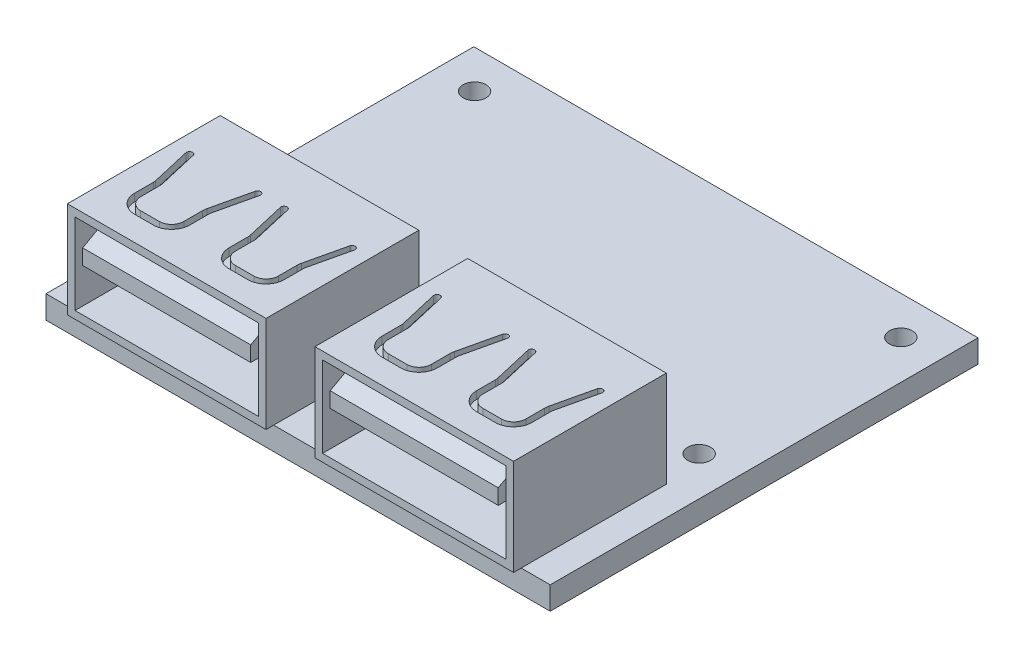
SolidWorks part; units mm, degrees
material "5V_BUCK_AVG"
ref_plane "Front Plane" through (0, 0, 0) normal (0, 0, 1) x (1, 0, 0)
ref_plane "Top Plane" through (0, 0, 0) normal (0, 1, 0) x (1, 0, 0)
ref_plane "Right Plane" through (0, 0, 0) normal (1, 0, 0) x (0, 0, -1)
sketch "Sketch1" plane through (0, 0, 0) normal (0, 1, 0) x (1, 0, 0)
  line L0 (-13.2, 4.318) -> (-13.2, 18.4768) construction
  line L1 (-16.5, -14) -> (16.5, -14)
  line L2 (-16.5, -14) -> (-16.5, 14)
  line L3 (-16.5, 14) -> (16.5, 14)
  line L4 (16.5, -14) -> (16.5, 14)
  line L5 (-16.5, -14) -> (16.5, 14) construction
  line L6 (-16.5, 14) -> (16.5, -14) construction
  line L7 (13.2, 0.5167) -> (13.2, 50000.5167) construction
  line L8 (-0.8528, 10.75) -> (49999.1472, 10.75) construction
  line L9 (-1.2363, -0.95) -> (49998.7637, -0.95) construction
  line L10 (0, 0) -> (50000, 0) construction
  line L11 (0, 0) -> (0, 50000) construction
  circle A0 centre (-13.95, 11.5) radius 0.75
  circle A1 centre (13.95, 11.5) radius 0.75
  circle A2 centre (13.95, -1.7) radius 0.75
  circle A3 centre (-13.95, -1.7) radius 0.75
  point P0 (0, 0)
  dimension "D3" = 1.5
  dimension "D1" = 33
  dimension "D2" = 28
  dimension "D4" = 26.4
  dimension "D5" = 11.7
  dimension "D6" = 2.5
extrude "Boss-Extrude1" add sketch "Sketch1" along normal blind 1.5
sketch "Sketch2" plane through (0, 1.5, 0) normal (0, 1, 0) x (1, 0, 0)
  line L0 (0, 0) -> (0, -50000) construction
  line L1 (-1.6, -4.5) -> (-14.6, -4.5)
  line L2 (-1.6, -4.5) -> (-1.6, -14.5)
  line L3 (-1.6, -14.5) -> (-14.6, -14.5)
  line L4 (-14.6, -4.5) -> (-14.6, -14.5)
  line L5 (-1.6, -4.5) -> (-14.6, -14.5) construction
  line L6 (-1.6, -14.5) -> (-14.6, -4.5) construction
  line L7 (-16.5, -14) -> (16.5, -14) construction
  point P0 (-8.1, -9.5)
  dimension "D1" = 13
  dimension "D2" = 10
  dimension "D3" = 1.6
  dimension "D4" = 0.5
extrude "Boss-Extrude2" add sketch "Sketch2" along normal blind 6.3
sketch "Sketch3" plane through (0, 0, 14.5) normal (0, 0, 1) x (1, 0, 0)
  line L0 (-14.1, 2) -> (-2.1, 2)
  line L1 (-2.1, 2) -> (-2.1, 7.3)
  line L2 (-2.1, 7.3) -> (-14.1, 7.3)
  line L3 (-14.1, 7.3) -> (-14.1, 2)
  line L4 (-14.6, 1.5) -> (-1.6, 1.5)
  line L5 (-1.6, 1.5) -> (-1.6, 7.8)
  line L6 (-1.6, 7.8) -> (-14.6, 7.8)
  line L7 (-14.6, 7.8) -> (-14.6, 1.5)
  line L8 (-14.6, 1.5) -> (-1.6, 1.5) construction
  line L9 (-1.6, 1.5) -> (-1.6, 7.8) construction
  line L10 (-1.6, 7.8) -> (-14.6, 7.8) construction
  line L11 (-14.6, 7.8) -> (-14.6, 1.5) construction
  dimension "D1" = 0
  dimension "D2" = 0.5
extrude "Cut-Extrude1" cut sketch "Sketch3" against normal offset from surface (9.5 mm away) 0.5 up to face at (-8.1, 4.65, 4.5)
sketch "Sketch4" plane through (0, 7.8, 0) normal (0, 1, 0) x (1, 0, 0)
  line L0 (-8.1, -4.5) -> (-8.1, -6.962) construction
  line L1 (-14.6, -4.5) -> (-14.6, -14) construction
  line L2 (-11.1939, -4.5) -> (-11.1939, -7.5186) construction
  line L3 (-13.4201, -7.6886) -> (-12.8274, -10.2519) construction
  line L4 (-12.8017, -10.4772) -> (-12.8017, -11.6975) construction
  line L5 (-11.8017, -12.6975) -> (-10.5861, -12.6975) construction
  line L6 (-9.5861, -10.4772) -> (-9.5861, -11.6975) construction
  line L7 (-8.9678, -7.6886) -> (-9.5604, -10.2519) construction
  line L8 (-13.6149, -7.7337) -> (-13.0223, -10.297)
  line L9 (-13.0017, -10.4772) -> (-13.0017, -11.6975)
  line L10 (-11.8017, -12.8975) -> (-10.5861, -12.8975)
  line L11 (-9.3861, -10.4772) -> (-9.3861, -11.6975)
  line L12 (-8.7729, -7.7337) -> (-9.3656, -10.297)
  line L13 (-13.2252, -7.6436) -> (-12.6325, -10.2069)
  line L14 (-12.6017, -10.4772) -> (-12.6017, -11.6975)
  line L15 (-11.8017, -12.4975) -> (-10.5861, -12.4975)
  line L16 (-9.7861, -10.4772) -> (-9.7861, -11.6975)
  line L17 (-9.1626, -7.6436) -> (-9.7553, -10.2069)
  line L18 (-7.2322, -7.6886) -> (-6.6396, -10.2519) construction
  line L19 (-6.6139, -10.4772) -> (-6.6139, -11.6975) construction
  line L20 (-4.3983, -12.6975) -> (-5.6139, -12.6975) construction
  line L21 (-3.3983, -10.4772) -> (-3.3983, -11.6975) construction
  line L22 (-2.7799, -7.6886) -> (-3.3726, -10.2519) construction
  line L23 (-7.0374, -7.6436) -> (-6.4447, -10.2069)
  line L24 (-6.4139, -10.4772) -> (-6.4139, -11.6975)
  line L25 (-4.3983, -12.4975) -> (-5.6139, -12.4975)
  line L26 (-3.5983, -10.4772) -> (-3.5983, -11.6975)
  line L27 (-2.9748, -7.6436) -> (-3.5675, -10.2069)
  line L28 (-7.4271, -7.7337) -> (-6.8344, -10.297)
  line L29 (-6.8139, -10.4772) -> (-6.8139, -11.6975)
  line L30 (-4.3983, -12.8975) -> (-5.6139, -12.8975)
  line L31 (-3.1983, -10.4772) -> (-3.1983, -11.6975)
  line L32 (-2.5851, -7.7337) -> (-3.1777, -10.297)
  arc A0 (-12.8017, -11.6975) -> (-11.8017, -12.6975) centre (-11.8017, -11.6975) ccw construction
  arc A1 (-12.8274, -10.2519) -> (-12.8017, -10.4772) centre (-13.8017, -10.4772) cw construction
  arc A2 (-9.5861, -11.6975) -> (-10.5861, -12.6975) centre (-10.5861, -11.6975) cw construction
  arc A3 (-9.5604, -10.2519) -> (-9.5861, -10.4772) centre (-8.5861, -10.4772) ccw construction
  arc A4 (-13.0223, -10.297) -> (-13.0017, -10.4772) centre (-13.8017, -10.4772) cw
  arc A5 (-13.0017, -11.6975) -> (-11.8017, -12.8975) centre (-11.8017, -11.6975) ccw
  arc A6 (-9.3861, -11.6975) -> (-10.5861, -12.8975) centre (-10.5861, -11.6975) cw
  arc A7 (-9.3656, -10.297) -> (-9.3861, -10.4772) centre (-8.5861, -10.4772) ccw
  arc A8 (-12.6325, -10.2069) -> (-12.6017, -10.4772) centre (-13.8017, -10.4772) cw
  arc A9 (-12.6017, -11.6975) -> (-11.8017, -12.4975) centre (-11.8017, -11.6975) ccw
  arc A10 (-9.7861, -11.6975) -> (-10.5861, -12.4975) centre (-10.5861, -11.6975) cw
  arc A11 (-9.7553, -10.2069) -> (-9.7861, -10.4772) centre (-8.5861, -10.4772) ccw
  arc A12 (-13.6149, -7.7337) -> (-13.2252, -7.6436) centre (-13.4201, -7.6886) cw
  arc A13 (-8.7729, -7.7337) -> (-9.1626, -7.6436) centre (-8.9678, -7.6886) ccw
  arc A14 (-6.6396, -10.2519) -> (-6.6139, -10.4772) centre (-7.6139, -10.4772) cw construction
  arc A15 (-6.6139, -11.6975) -> (-5.6139, -12.6975) centre (-5.6139, -11.6975) ccw construction
  arc A16 (-3.3726, -10.2519) -> (-3.3983, -10.4772) centre (-2.3983, -10.4772) ccw construction
  arc A17 (-3.3983, -11.6975) -> (-4.3983, -12.6975) centre (-4.3983, -11.6975) cw construction
  arc A18 (-7.4271, -7.7337) -> (-7.0374, -7.6436) centre (-7.2322, -7.6886) cw
  arc A19 (-2.5851, -7.7337) -> (-2.9748, -7.6436) centre (-2.7799, -7.6886) ccw
  arc A20 (-6.4447, -10.2069) -> (-6.4139, -10.4772) centre (-7.6139, -10.4772) cw
  arc A21 (-6.4139, -11.6975) -> (-5.6139, -12.4975) centre (-5.6139, -11.6975) ccw
  arc A22 (-3.5983, -11.6975) -> (-4.3983, -12.4975) centre (-4.3983, -11.6975) cw
  arc A23 (-3.5675, -10.2069) -> (-3.5983, -10.4772) centre (-2.3983, -10.4772) ccw
  arc A24 (-6.8344, -10.297) -> (-6.8139, -10.4772) centre (-7.6139, -10.4772) cw
  arc A25 (-6.8139, -11.6975) -> (-5.6139, -12.8975) centre (-5.6139, -11.6975) ccw
  arc A26 (-3.1983, -11.6975) -> (-4.3983, -12.8975) centre (-4.3983, -11.6975) cw
  arc A27 (-3.1777, -10.297) -> (-3.1983, -10.4772) centre (-2.3983, -10.4772) ccw
  point P15 (-11.1939, -12.6975)
  point P65 (-5.0061, -12.6975)
  dimension "D3" = 1
  dimension "D1" = 6.5
  dimension "D2" = 3.0939
  dimension "D4" = 0.2
  dimension "D5" = 0.2
extrude "Cut-Extrude2" cut sketch "Sketch4" against normal up to next
sketch "Sketch5" plane through (0, 0, 5) normal (0, 0, 1) x (1, 0, 0)
  line L0 (-8.1, 7.8) -> (-8.1, -49992.2) construction
  line L1 (-14.6, 7.8) -> (-1.6, 7.8) construction
  line L2 (-14.1, 7.3) -> (-2.1, 7.3) construction
  line L3 (-13.6, 4.8) -> (-2.6, 4.8)
  line L4 (-13.6, 4.8) -> (-13.6, 6.8)
  line L5 (-13.6, 6.8) -> (-2.6, 6.8)
  line L6 (-2.6, 4.8) -> (-2.6, 6.8)
  line L7 (-13.6, 4.8) -> (-2.6, 6.8) construction
  line L8 (-13.6, 6.8) -> (-2.6, 4.8) construction
  point P4 (-8.1, 7.8)
  point P5 (-8.1, 5.8)
  dimension "D1" = 2
  dimension "D2" = 0.5
  dimension "D3" = 11
extrude "Boss-Extrude3" add sketch "Sketch5" along normal up to surface (9.5 mm away) up to face at (-8.1, 4.65, 14.5)
chamfer "Chamfer1" distance 1 angle 61 1 edges at (-8.1, 6.8, 14.5)
mirror "Mirror4" about plane through (0, 0, 0) normal (1, 0, 0) of "Cut-Extrude1", "Cut-Extrude2", "Boss-Extrude3", "Chamfer1", "Boss-Extrude2"
